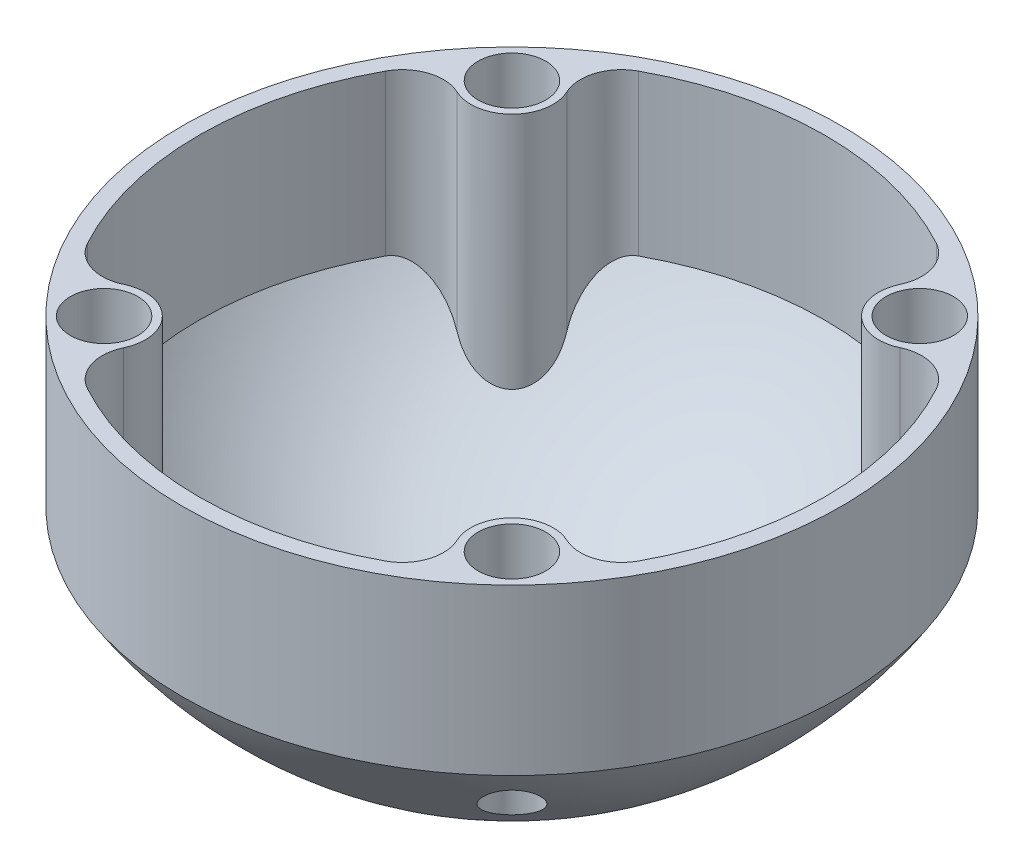
SolidWorks part; units mm, degrees
ref_plane "Alzado" through (0, 0, 0) normal (0, 0, 1) x (1, 0, 0)
ref_plane "Planta" through (0, 0, 0) normal (0, 1, 0) x (1, 0, 0)
ref_plane "Vista lateral" through (0, 0, 0) normal (1, 0, 0) x (0, 0, -1)
sketch "Sketch1" plane through (0, 0, 0) normal (0, 0, 1) x (1, 0, 0)
  line L0 (0, 0) -> (0, 60) construction
  line L1 (0, 60) -> (40, 60) construction
  line L2 (0, 45.0231) -> (0, 60)
  line L3 (0, 60) -> (40, 60)
  arc A2 (40, 60) -> (0, 45.0231) centre (3.4475, 96.7197) cw
  dimension "D1" = 60
  dimension "D2" = 40
sketch "Sketch8" plane through (0, 0, 0) normal (0, 0, 1) x (1, 0, 0)
  line L0 (0, 0) -> (0, 60) construction
  line L1 (-40, 60) -> (0, 60)
  line L2 (0, 60) -> (0, 16.1919)
  line L3 (-40, 60) -> (-40, 39.9781)
  arc A1 (-40, 39.9781) -> (0, 16.1919) centre (3.2859, 67.2436) ccw
revolve "Revolve1" add sketch "Sketch8" angle 360 about L2
shell "Shell1" thickness 2
sketch "Sketch9" plane through (0, 60, 0) normal (0, 1, 0) x (1, 0, 0)
  arc A1 (-23.7657, -29.6512) -> (-29.6512, -23.7657) centre (-24.7487, -24.7487) ccw
  arc A2 (-29.6512, -23.7657) -> (-23.7657, -29.6512) centre (0, 0) ccw
  arc A3 (-29.6512, 23.7657) -> (-23.7657, 29.6512) centre (-24.7487, 24.7487) ccw
  arc A4 (-23.7657, 29.6512) -> (-29.6512, 23.7657) centre (0, 0) ccw
  arc A5 (23.7657, 29.6512) -> (29.6512, 23.7657) centre (24.7487, 24.7487) ccw
  arc A6 (29.6512, 23.7657) -> (23.7657, 29.6512) centre (0, 0) ccw
  arc A7 (29.6512, -23.7657) -> (23.7657, -29.6512) centre (24.7487, -24.7487) ccw
  arc A8 (23.7657, -29.6512) -> (29.6512, -23.7657) centre (0, 0) ccw
  point P18 (0, 0)
  dimension "D1" = 4
extrude "Boss-Extrude1" add sketch "Sketch9" against normal up to surface (19.4382 mm away)
sketch "Sketch10" plane through (0, 60, 0) normal (0, 1, 0) x (1, 0, 0)
  circle A0 centre (-24.7487, -24.7487) radius 1.6
  circle A1 centre (-24.7487, 24.7487) radius 1.6
  circle A2 centre (24.7487, 24.7487) radius 1.6
  circle A3 centre (24.7487, -24.7487) radius 1.6
  point P12 (0, 0)
  dimension "D2" = 3.2
  dimension "D1" = 4
fillet "Fillet1" radius 5 8 edges at (29.6512, 50.2809, 23.7657) (23.7657, 50.2809, 29.6512) (23.7657, 50.2809, -29.6512) (29.6512, 50.2809, -23.7657) (-29.6512, 50.2809, -23.7657) (-23.7657, 50.2809, -29.6512) (-23.7657, 50.2809, 29.6512) (-29.6512, 50.2809, 23.7657)
sketch "Sketch11" plane through (0, 60, 0) normal (0, 1, 0) x (1, 0, 0)
  circle A0 centre (-24.7487, 24.7487) radius 4.1
  circle A1 centre (24.7487, 24.7487) radius 4.1
  circle A2 centre (24.7487, -24.7487) radius 4.1
  circle A3 centre (-24.7487, -24.7487) radius 4.1
  point P12 (0, 0)
  dimension "D1" = 8.2
extrude "Cut-Extrude1" cut sketch "Sketch11" against normal blind 10
sketch "Sketch13" plane through (0, 0, 0) normal (0, 1, 0) x (1, 0, 0)
  circle A0 centre (-24.7487, 24.7487) radius 3
  circle A1 centre (24.7487, 24.7487) radius 3
  circle A2 centre (24.7487, -24.7487) radius 3
  circle A3 centre (-24.7487, -24.7487) radius 3
  point P12 (0, 0)
  dimension "D1" = 6
extrude "Cut-Extrude3" cut sketch "Sketch13" along normal blind 23 from offset 25
extrude "Cut-Extrude4" cut sketch "Sketch10" against normal blind 19
